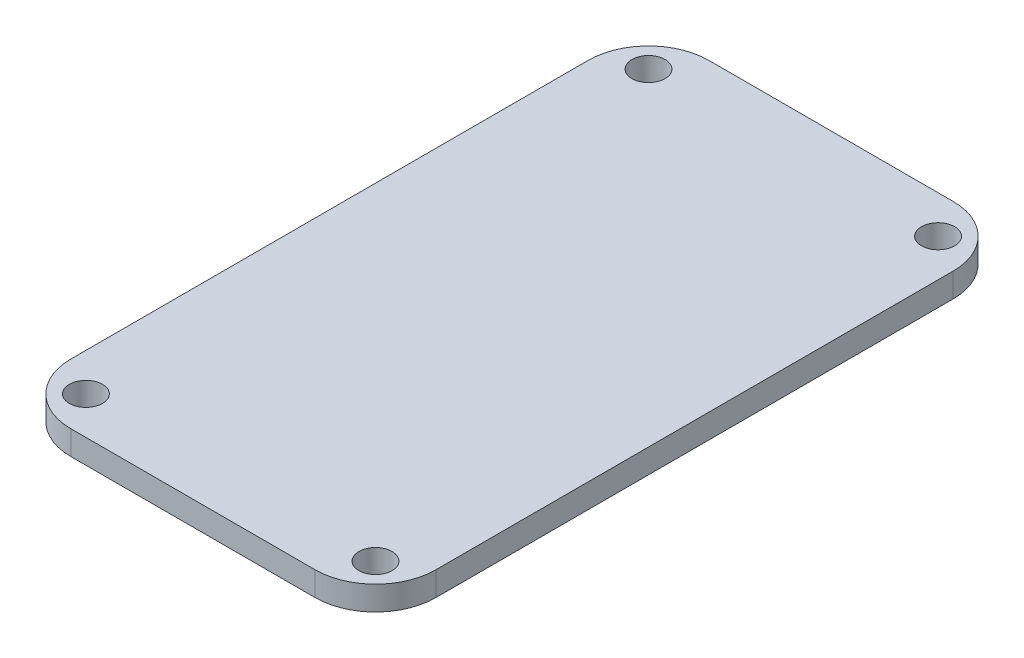
SolidWorks part; units mm, degrees
ref_plane "前视基准面" through (0, 0, 0) normal (0, 0, 1) x (1, 0, 0)
ref_plane "上视基准面" through (0, 0, 0) normal (0, 1, 0) x (1, 0, 0)
ref_plane "右视基准面" through (0, 0, 0) normal (1, 0, 0) x (0, 0, -1)
other "Configuration Table"
sketch "草图1" plane through (0, 0, 0) normal (0, 1, 0) x (1, 0, 0)
  line L1 (-12.1, -21.15) -> (12.1, -21.15)
  line L2 (-12.1, -21.15) -> (-12.1, 21.15)
  line L3 (-12.1, 21.15) -> (12.1, 21.15)
  line L4 (12.1, -21.15) -> (12.1, 21.15)
  line L5 (0, 21.15) -> (0, -21.15) construction
  line L6 (-12.1, 0) -> (12.1, 0) construction
  point P0 (0, 0)
  dimension "D1" = 24.2
  dimension "D2" = 42.3
extrude "凸台-拉伸1" add sketch "草图1" along normal blind 1.6
fillet "圆角1" radius 4 4 edges at (-12.1, 0.8, 21.15) (-12.1, 0.8, -21.15) (12.1, 0.8, -21.15) (12.1, 0.8, 21.15)
sketch "草图2" plane through (0, 1.6, 0) normal (0, 1, 0) x (1, 0, 0)
  line L0 (8.1, 21.15) -> (-8.1, 21.15) construction
  line L1 (-9.6, -18.65) -> (9.6, -18.65) construction
  line L2 (-9.6, -18.65) -> (-9.6, 18.65) construction
  line L3 (-9.6, 18.65) -> (9.6, 18.65) construction
  line L4 (9.6, -18.65) -> (9.6, 18.65) construction
  line L5 (0, 18.65) -> (0, -18.65) construction
  line L6 (-9.6, 0) -> (9.6, 0) construction
  line L8 (-12.1, 17.15) -> (-12.1, -17.15) construction
  circle A0 centre (-9.6, 18.65) radius 1.1
  circle A1 centre (9.6, 18.65) radius 1.1
  circle A2 centre (9.6, -18.65) radius 1.1
  circle A3 centre (-9.6, -18.65) radius 1.1
  point P0 (0, 0)
  dimension "D1" = 2.2
  dimension "D2" = 2.5
  dimension "D3" = 2.5
extrude "切除-拉伸1" cut sketch "草图2" against normal through all and the other way through all
